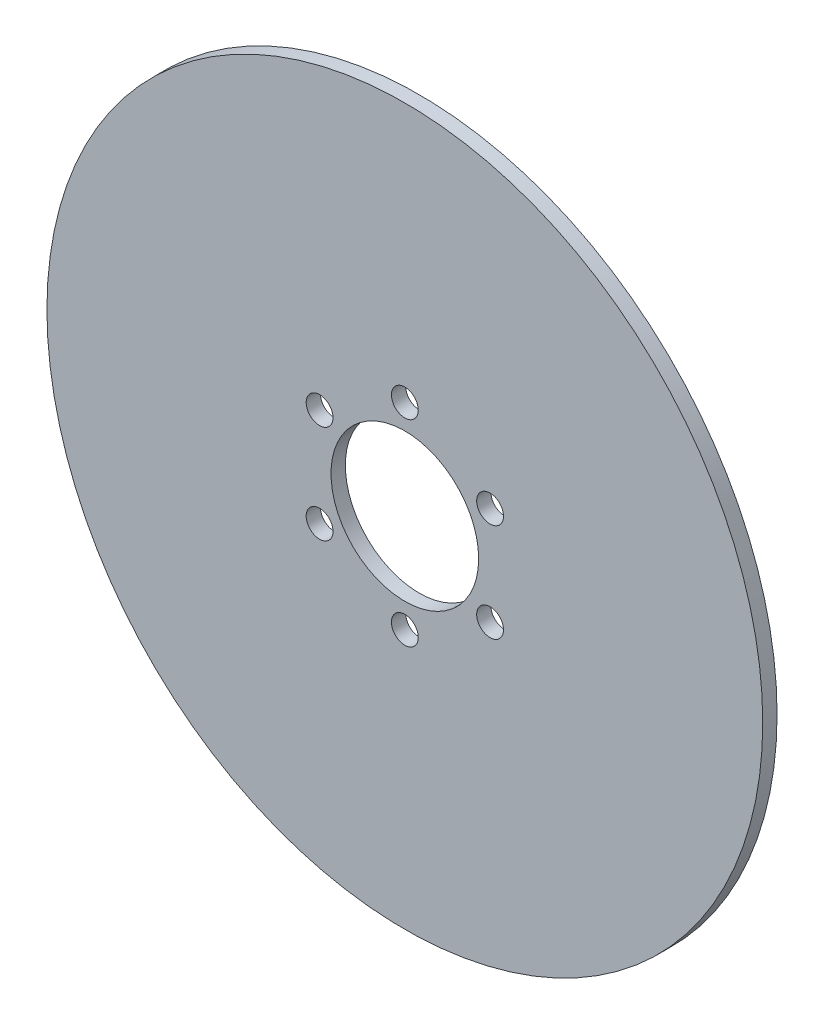
SolidWorks part; units mm, degrees
ref_plane "Plan de face" through (0, 0, 0) normal (0, 0, 1) x (1, 0, 0)
ref_plane "Plan de dessus" through (0, 0, 0) normal (0, 1, 0) x (1, 0, 0)
ref_plane "Plan de droite" through (0, 0, 0) normal (1, 0, 0) x (0, 0, -1)
sketch "Esquisse1" plane through (0, 0, 0) normal (0, 0, 1) x (1, 0, 0)
  circle A1 centre (0, 22) radius 3
  circle A2 centre (0, 0) radius 16.5
  circle A3 centre (19.0526, 11) radius 3
  circle A4 centre (19.0526, -11) radius 3
  circle A5 centre (0, -22) radius 3
  circle A6 centre (-19.0526, -11) radius 3
  circle A7 centre (-19.0526, 11) radius 3
  circle A8 centre (0, 0) radius 80
  circle A9 centre (0, 68) radius 10
  circle A10 centre (26.0225, 62.8238) radius 10
  circle A11 centre (48.0833, 48.0833) radius 10
  circle A12 centre (62.8238, 26.0225) radius 10
  circle A13 centre (68, 0) radius 10
  circle A14 centre (62.8238, -26.0225) radius 10
  circle A15 centre (48.0833, -48.0833) radius 10
  circle A16 centre (26.0225, -62.8238) radius 10
  circle A17 centre (0, -68) radius 10
  circle A18 centre (-26.0225, -62.8238) radius 10
  circle A19 centre (-48.0833, -48.0833) radius 10
  circle A20 centre (-62.8238, -26.0225) radius 10
  circle A21 centre (-68, 0) radius 10
  circle A22 centre (-62.8238, 26.0225) radius 10
  circle A23 centre (-48.0833, 48.0833) radius 10
  circle A24 centre (-26.0225, 62.8238) radius 10
  point P18 (0, 0)
  point P52 (0, 0)
  dimension "D1" = 22
  dimension "D2" = 33
  dimension "D3" = 6
  dimension "D5" = 160
  dimension "D6" = 20
  dimension "D8" = 16
  dimension "D7" = 68
  dimension "D4" = 6
extrude "Boss.-Extru.1" add sketch "Esquisse1" along normal blind 3.2
sketch "Esquisse2" plane through (0, 0, 3.2) normal (0, 0, 1) x (1, 0, 0)
  circle A0 centre (0, 0) radius 53.2536
  circle A1 centre (0, 0) radius 80
extrude "Boss.-Extru.2" add sketch "Esquisse2" against normal blind 0.2
